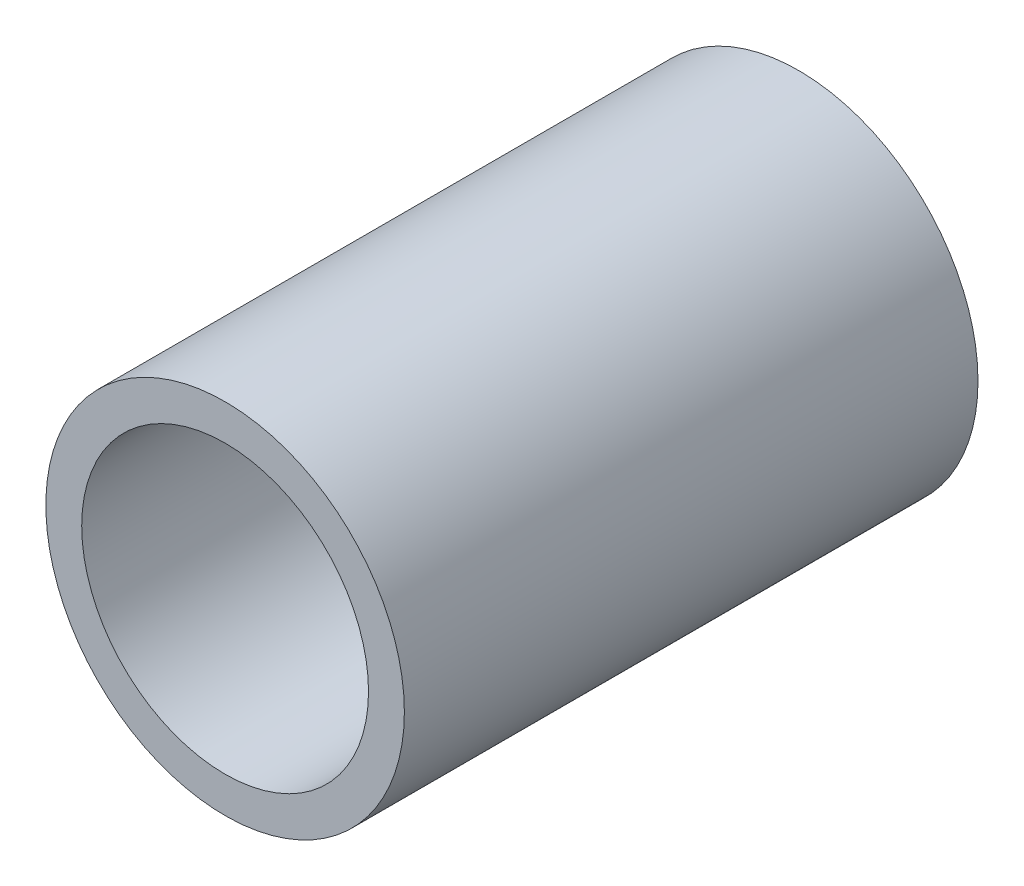
SolidWorks part; units mm, degrees
material "Leaded Commercial Bronze"
ref_plane "Front Plane" through (0, 0, 0) normal (0, 0, 1) x (1, 0, 0)
ref_plane "Top Plane" through (0, 0, 0) normal (0, 1, 0) x (1, 0, 0)
ref_plane "Right Plane" through (0, 0, 0) normal (1, 0, 0) x (0, 0, -1)
sketch "Sketch1" plane through (0, 0, 0) normal (0, 0, 1) x (1, 0, 0)
  circle A0 centre (0, 0) radius 7.9375
  circle A1 centre (0, 0) radius 6.35
  dimension "D1" = 12.7
  dimension "D2" = 15.875
extrude "Boss-Extrude1" add sketch "Sketch1" along normal blind 25.4
